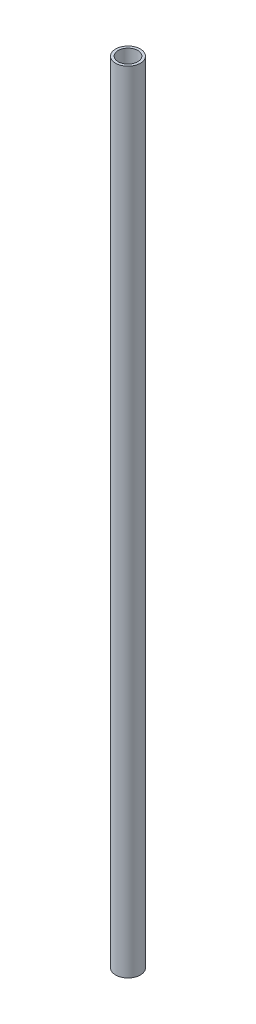
SolidWorks part; units mm, degrees
ref_plane "Front Plane" through (0, 0, 0) normal (0, 0, 1) x (1, 0, 0)
ref_plane "Top Plane" through (0, 0, 0) normal (0, 1, 0) x (1, 0, 0)
ref_plane "Right Plane" through (0, 0, 0) normal (1, 0, 0) x (0, 0, -1)
sketch "Sketch1" plane through (0, 0, 0) normal (0, 1, 0) x (1, 0, 0)
  circle A0 centre (0, 0) radius 7.9375
  circle A1 centre (0, 0) radius 6.2865
  dimension "D1" = 15.875
  dimension "D2" = 1.651
extrude "Boss-Extrude1" add sketch "Sketch1" along normal blind 507
